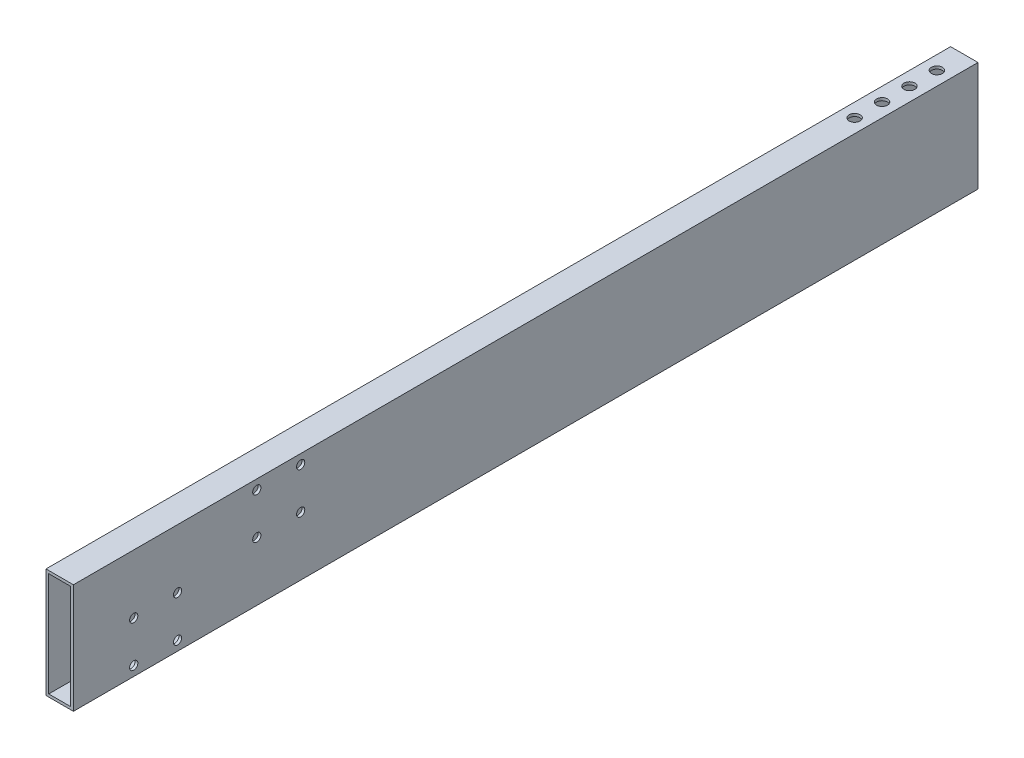
SolidWorks part; units mm, degrees
material "3.0205 (EN-AW 1200)"
ref_plane "前视基准面" through (0, 0, 0) normal (0, 0, 1) x (1, 0, 0)
ref_plane "上视基准面" through (0, 0, 0) normal (0, 1, 0) x (1, 0, 0)
ref_plane "右视基准面" through (0, 0, 0) normal (1, 0, 0) x (0, 0, -1)
sketch "草图1" plane through (0, 0, 0) normal (0, 0, 1) x (1, 0, 0)
  line L1 (0, 0) -> (10, 0)
  line L2 (0, 0) -> (0, 40)
  line L3 (0, 40) -> (10, 40)
  line L4 (10, 0) -> (10, 40)
  line L5 (1, 1) -> (9, 1)
  line L6 (1, 1) -> (1, 39)
  line L7 (1, 39) -> (9, 39)
  line L8 (9, 1) -> (9, 39)
  dimension "D1" = 10
  dimension "D2" = 40
  dimension "D3" = 1
  dimension "D4" = 1
  dimension "D5" = 1
  dimension "D6" = 1
extrude "凸台-拉伸1" add sketch "草图1" along normal blind 330
sketch "草图3" plane through (10, 0, 0) normal (1, 0, 0) x (0, 0, -1)
  line L0 (-330, 0) -> (-330, 40) construction
  line L1 (-308, 18.5) -> (-292, 18.5) construction
  line L2 (-308, 18.5) -> (-308, 3.5) construction
  line L3 (-308, 3.5) -> (-292, 3.5) construction
  line L4 (-292, 18.5) -> (-292, 3.5) construction
  line L5 (-330, 0) -> (0, 0) construction
  line L7 (-263.1, 36.5) -> (-247.1, 36.5) construction
  line L8 (-263.1, 36.5) -> (-263.1, 21.5) construction
  line L9 (-263.1, 21.5) -> (-247.1, 21.5) construction
  line L10 (-247.1, 36.5) -> (-247.1, 21.5) construction
  circle A0 centre (-308, 18.5) radius 1.5
  circle A1 centre (-292, 18.5) radius 1.5
  circle A2 centre (-292, 3.5) radius 1.5
  circle A3 centre (-308, 3.5) radius 1.5
  circle A4 centre (-263.1, 36.5) radius 1.5
  circle A5 centre (-247.1, 36.5) radius 1.5
  circle A6 centre (-263.1, 21.5) radius 1.5
  circle A7 centre (-247.1, 21.5) radius 1.5
  dimension "D5" = 3
  dimension "D6" = 3
  dimension "D7" = 3
  dimension "D8" = 3
  dimension "D13" = 3
  dimension "D14" = 3
  dimension "D15" = 3
  dimension "D16" = 3
  dimension "D1" = 22
  dimension "D2" = 16
  dimension "D3" = 15
  dimension "D4" = 3.5
  dimension "D9" = 3
  dimension "D10" = 28.9
  dimension "D11" = 16
  dimension "D12" = 15
extrude "切除-拉伸2" cut sketch "草图3" against normal blind 10
sketch "草图4" plane through (0, 40, 0) normal (0, 1, 0) x (1, 0, 0)
  line L0 (5, 0) -> (5, -56.463) construction
  line L2 (10, 0) -> (0, 0) construction
  circle A3 centre (5, -10) radius 2
  circle A4 centre (5, -20) radius 2
  circle A5 centre (5, -30) radius 2
  circle A6 centre (5, -40) radius 2
  dimension "D1" = 4
  dimension "D2" = 10
  dimension "D3" = 3
  dimension "D4" = 2
extrude "切除-拉伸4" cut sketch "草图4" against normal through all both and the other way through all
